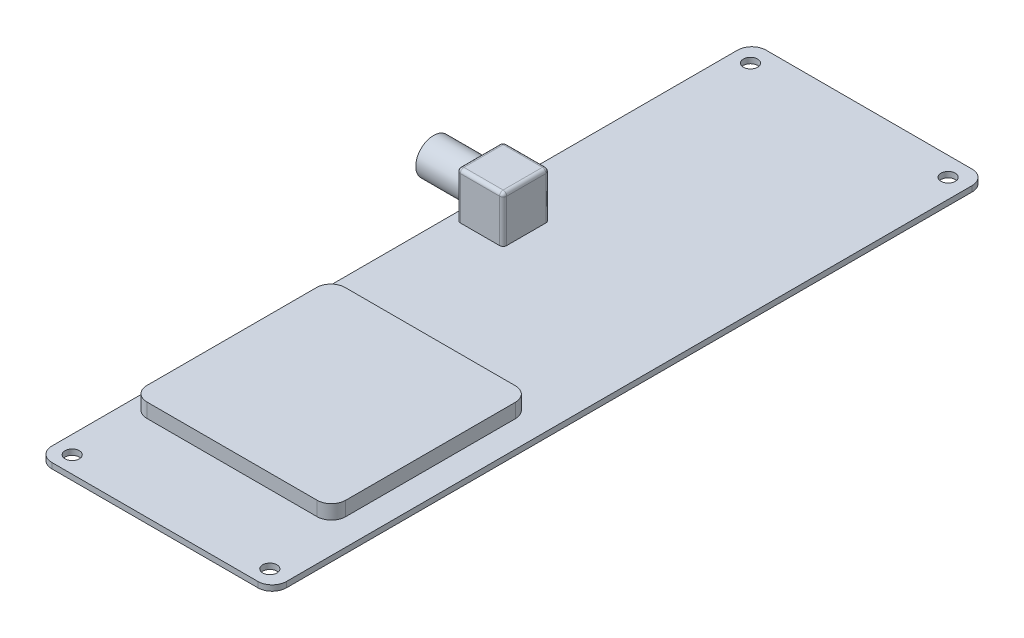
SolidWorks part; units mm, degrees
ref_plane "Front Plane" through (0, 0, 0) normal (0, 0, 1) x (1, 0, 0)
ref_plane "Top Plane" through (0, 0, 0) normal (0, 1, 0) x (1, 0, 0)
ref_plane "Right Plane" through (0, 0, 0) normal (1, 0, 0) x (0, 0, -1)
sketch "Sketch1" plane through (0, 0, 0) normal (0, 1, 0) x (1, 0, 0)
  line L1 (-14.445, -50.065) -> (14.445, -50.065)
  line L2 (-16.445, -48.065) -> (-16.445, 48.065)
  line L3 (-14.445, 50.065) -> (14.445, 50.065)
  line L4 (16.445, -48.065) -> (16.445, 48.065)
  circle A0 centre (-13.9573, 47.395) radius 1
  circle A1 centre (13.7527, 47.395) radius 1
  circle A2 centre (13.7527, -47.705) radius 1
  circle A3 centre (-13.9573, -47.705) radius 1
  arc A4 (-16.445, 48.065) -> (-14.445, 50.065) centre (-14.445, 48.065) cw
  arc A5 (14.445, 50.065) -> (16.445, 48.065) centre (14.445, 48.065) cw
  arc A6 (14.445, -50.065) -> (16.445, -48.065) centre (14.445, -48.065) ccw
  arc A7 (-14.445, -50.065) -> (-16.445, -48.065) centre (-14.445, -48.065) cw
  point P15 (-16.445, 50.065)
  point P20 (16.445, -50.065)
  point P23 (-16.445, -50.065)
  dimension "D6" = 2
  dimension "D11" = 2
  dimension "D1" = 100.13
  dimension "D2" = 32.89
  dimension "D5" = 2.67
  dimension "D7" = 27.71
  dimension "D8" = 95.1
  dimension "D9" = 50.065
  dimension "D10" = 16.445
  dimension "D3" = 2
  dimension "D4" = 2
extrude "Boss-Extrude1" add sketch "Sketch1" along normal blind 0.78
sketch "Sketch2" plane through (0, 0.78, 0) normal (0, 1, 0) x (1, 0, 0)
  line L1 (-15.3956, 14.1499) -> (-8.8956, 14.1499)
  line L2 (-15.3956, 14.1499) -> (-15.3956, 7.6499)
  line L3 (-15.3956, 7.6499) -> (-8.8956, 7.6499)
  line L4 (-8.8956, 14.1499) -> (-8.8956, 7.6499)
  dimension "D1" = 6.5
  dimension "D2" = 6.5
extrude "Boss-Extrude2" add sketch "Sketch2" along normal blind 6.5
fillet "Fillet1" radius 0.5 8 edges at (-8.8956, 4.03, -14.1499) (-15.3956, 4.03, -14.1499) (-15.3956, 7.28, -10.8999) (-15.3956, 4.03, -7.6499) (-8.8956, 7.28, -10.8999) (-12.1456, 7.28, -7.6499) (-8.8956, 4.03, -7.6499) (-12.1456, 7.28, -14.1499)
sketch "Sketch3" plane through (-15.3956, 0, 0) normal (-1, 0, 0) x (0, 0, 1)
  line L0 (-10.8999, 7.28) -> (-10.8999, 0.78) construction
  line L1 (-13.6499, 7.28) -> (-8.1499, 7.28) construction
  line L2 (-13.6499, 0.78) -> (-8.1499, 0.78) construction
  line L3 (-14.1499, 3.78) -> (-7.6499, 3.78) construction
  line L4 (-14.1499, 0.78) -> (-14.1499, 6.78) construction
  line L5 (-7.6499, 6.78) -> (-7.6499, 0.78) construction
  circle A0 centre (-10.8999, 3.78) radius 2.5
  point P14 (-10.8999, 3.78)
  dimension "D1" = 5
extrude "Boss-Extrude3" add sketch "Sketch3" along normal blind 6.5
cosmetic thread "Cosmetic Thread1" parameters "D1"=4.5, "D2"=4.11
sketch "Sketch4" plane through (0, 0.78, 0) normal (0, 1, 0) x (1, 0, 0)
  line L1 (-13.1352, -10.2598) -> (10.7372, -10.2598)
  line L2 (-15.1352, -12.2598) -> (-15.1352, -36.0563)
  line L3 (-13.1352, -38.0563) -> (10.7372, -38.0563)
  line L4 (12.7372, -12.2598) -> (12.7372, -36.0563)
  arc A0 (10.7372, -38.0563) -> (12.7372, -36.0563) centre (10.7372, -36.0563) ccw
  arc A1 (10.7372, -10.2598) -> (12.7372, -12.2598) centre (10.7372, -12.2598) cw
  arc A2 (-15.1352, -36.0563) -> (-13.1352, -38.0563) centre (-13.1352, -36.0563) ccw
  arc A3 (-13.1352, -10.2598) -> (-15.1352, -12.2598) centre (-13.1352, -12.2598) ccw
  dimension "D1" = 2
extrude "Boss-Extrude4" add sketch "Sketch4" along normal blind 2
